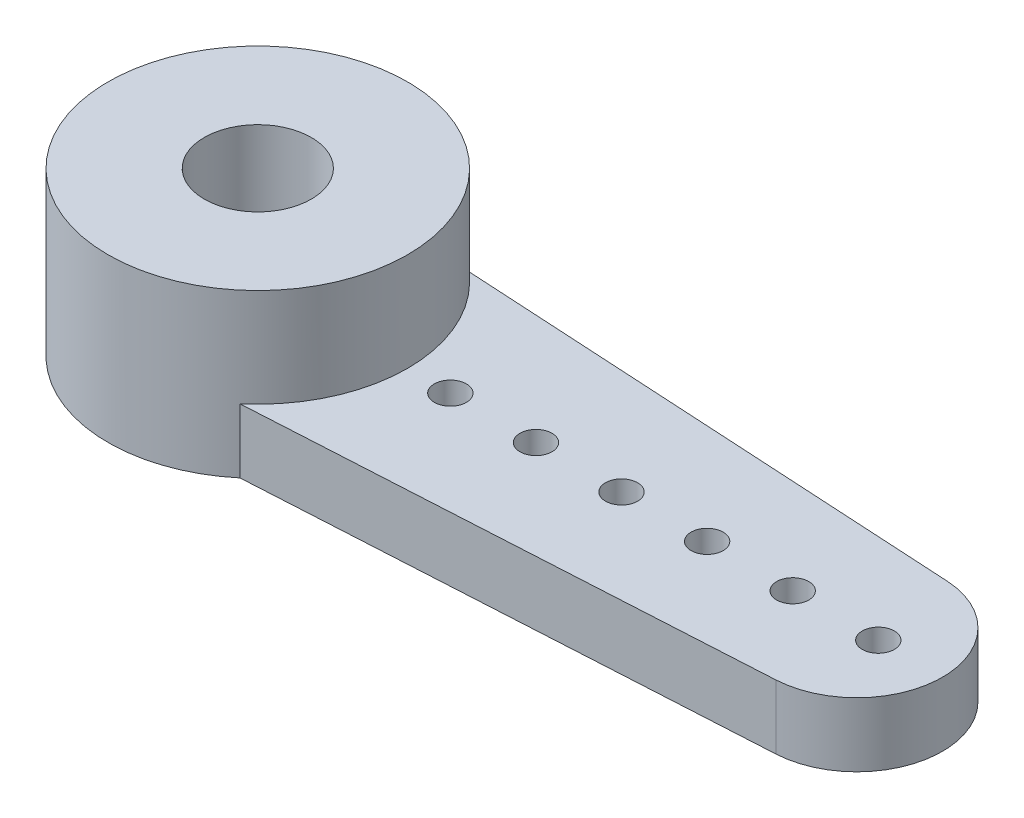
SolidWorks part; units mm, degrees
ref_plane "Front Plane" through (0, 0, 0) normal (0, 0, 1) x (1, 0, 0)
ref_plane "Top Plane" through (0, 0, 0) normal (0, 1, 0) x (1, 0, 0)
ref_plane "Right Plane" through (0, 0, 0) normal (1, 0, 0) x (0, 0, -1)
sketch "Sketch1" plane through (0, 0, 0) normal (0, 1, 0) x (1, 0, 0)
  line L0 (2.2571, 2.675) -> (14.1106, 2)
  line L1 (0, 0) -> (13.9968, 0) construction
  line L2 (14.1106, -2) -> (2.2571, -2.675)
  line L3 (0, 3.5) -> (0, -3.5) construction
  arc A0 (2.2571, 2.675) -> (2.2571, -2.675) centre (0, 0) ccw
  arc A1 (14.1106, 2) -> (14.1106, -2) centre (13.9968, 0) cw
  point P11 (-3.5, 0)
  point P12 (16, 0)
  dimension "D1" = 4
  dimension "D2" = 7
  dimension "D3" = 5.35
  dimension "D4" = 19.5
extrude "Boss-Extrude1" add sketch "Sketch1" along normal blind 1.5
sketch "Sketch2" plane through (0, 1.5, 0) normal (0, 1, 0) x (1, 0, 0)
  circle A0 centre (0, 0) radius 3.5
  arc A1 (2.2571, 2.675) -> (2.2571, -2.675) centre (0, 0) ccw construction
extrude "Boss-Extrude2" add sketch "Sketch2" along normal offset from surface (2.3 mm away) 3.8 up to face at (7.2169, 0, 0)
sketch "Sketch3" plane through (0, 1.5, 0) normal (0, 1, 0) x (1, 0, 0)
  circle A1 centre (4.5, 0) radius 0.375
  circle A8 centre (0, 0) radius 1.25
  circle A10 centre (6.5, 0) radius 0.375
  circle A11 centre (8.5, 0) radius 0.375
  circle A12 centre (10.5, 0) radius 0.375
  circle A13 centre (12.5, 0) radius 0.375
  circle A14 centre (14.5, 0) radius 0.375
  point P0 (14.5, 0)
  dimension "D1" = 0.75
  dimension "D3" = 2.5
  dimension "D4" = 2
  dimension "D2" = 4.5
extrude "Cut-Extrude1" cut sketch "Sketch3" against normal through all both and the other way through all
